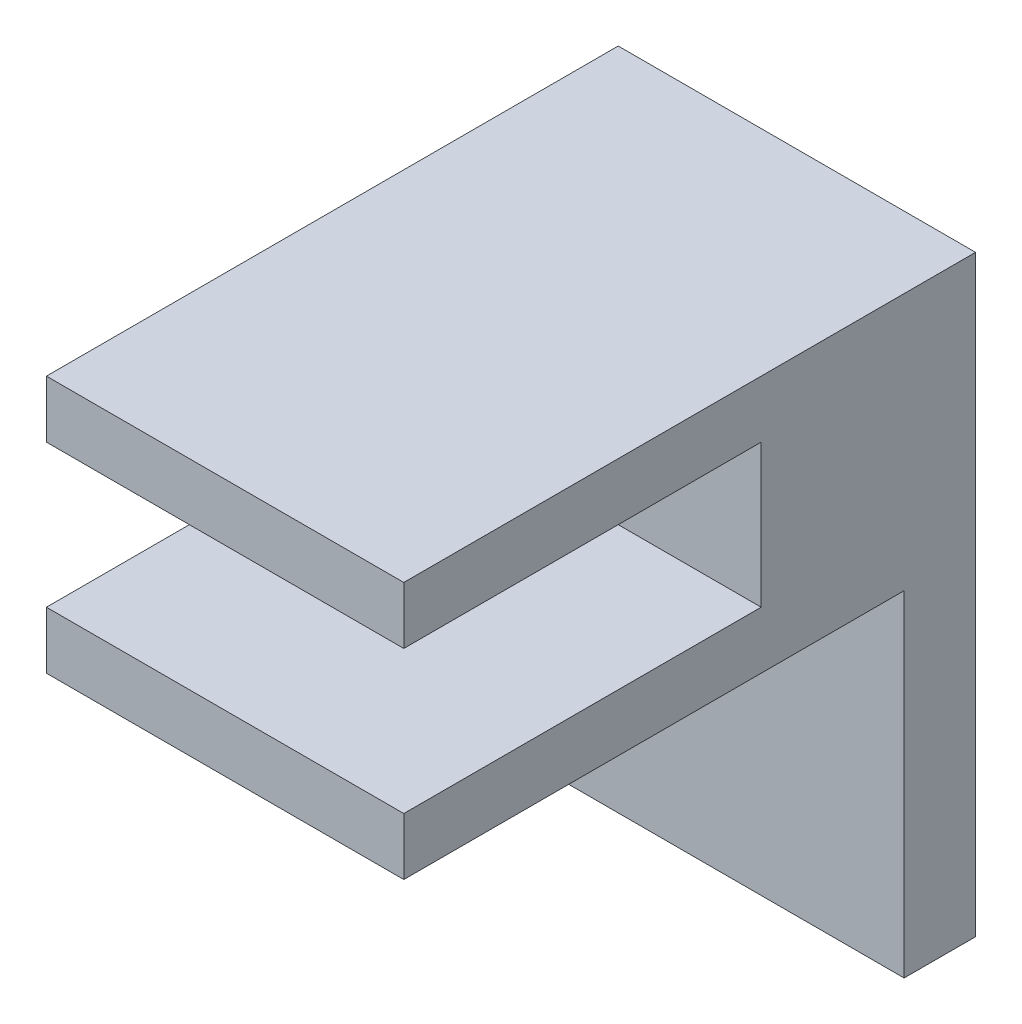
SolidWorks part; units mm, degrees
ref_plane "前视基准面" through (0, 0, 0) normal (0, 0, 1) x (1, 0, 0)
ref_plane "上视基准面" through (0, 0, 0) normal (0, 1, 0) x (1, 0, 0)
ref_plane "右视基准面" through (0, 0, 0) normal (1, 0, 0) x (0, 0, -1)
sketch "草图1" plane through (0, 0, 0) normal (1, 0, 0) x (0, 0, -1)
  line L0 (-40, 14.8277) -> (-40, 18.8277)
  line L1 (-5, 0.8277) -> (-40, 0.8277)
  line L2 (0, 0) -> (0, 18.8277)
  line L3 (0, 18.8277) -> (-40, 18.8277)
  line L4 (-40, 0.8277) -> (-40, 4.8277)
  line L5 (-40, 14.8277) -> (-15, 14.8277)
  line L7 (-40, 4.8277) -> (-15, 4.8277)
  line L8 (-15, 14.8277) -> (-15, 4.8277)
  line L10 (-5, 0.8277) -> (-5, -22.6368)
  line L11 (-5, -22.6368) -> (0, -22.6368)
  line L12 (0, 0) -> (0, -22.6368)
  dimension "D1" = 25
  dimension "D2" = 10
  dimension "D3" = 4
  dimension "D4" = 15
  dimension "D5" = 5
extrude "凸台-拉伸1" add sketch "草图1" along normal mid plane 25
